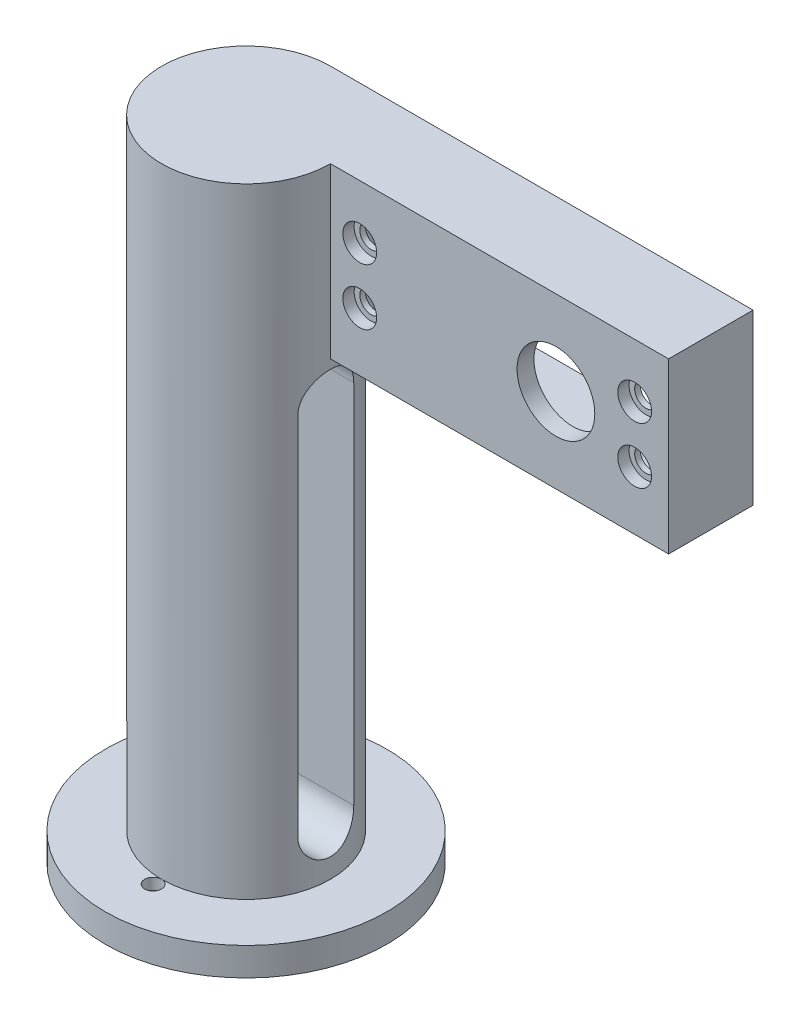
SolidWorks part; units mm, degrees
ref_plane "Front Plane" through (0, 0, 0) normal (0, 0, 1) x (1, 0, 0)
ref_plane "Top Plane" through (0, 0, 0) normal (0, 1, 0) x (1, 0, 0)
ref_plane "Right Plane" through (0, 0, 0) normal (1, 0, 0) x (0, 0, -1)
sketch "Sketch1" plane through (0, 0, 0) normal (0, 1, 0) x (1, 0, 0)
  circle A0 centre (0, 0) radius 25
  dimension "D1" = 50
extrude "Boss-Extrude1" add sketch "Sketch1" along normal blind 5 contours A0
sketch "Sketch2" plane through (0, 5, 0) normal (0, 1, 0) x (1, 0, 0)
  circle A0 centre (0, 0) radius 15
extrude "Boss-Extrude2" add sketch "Sketch2" along normal blind 95 contours A0
sketch "Sketch5" plane through (0, 100, 0) normal (0, 1, 0) x (1, 0, 0)
  line L5 (75, 0) -> (15, 0)
  line L6 (0, 15) -> (75, 15)
  line L9 (75, 15) -> (75, 0)
  arc A4 (0, 15) -> (15, 0) centre (0, 0) ccw
  circle A5 centre (0, 0) radius 15 construction
  circle A6 centre (0, 0) radius 15 construction
  point P2 (0, 0)
  point P20 (0, 0)
extrude "Boss-Extrude4" add sketch "Sketch5" along normal mid plane 30 contours L5 A4 L6 L9
sketch "Sketch10" plane through (0, 0, 0) normal (0, 0, 1) x (1, 0, 0)
  line L0 (15, 100) -> (55, 100) construction
  line L1 (15, 115) -> (15, 85) construction
  line L2 (16.68, 110.4) -> (16.68, 90.4)
  line L3 (16.68, 90.4) -> (72.68, 90.4)
  line L4 (72.68, 90.4) -> (72.68, 110.4)
  line L5 (72.68, 110.4) -> (16.68, 110.4)
  circle A0 centre (55, 100) radius 6.5
  point P5 (0, 100)
  point P6 (68.98, 95.4)
  point P7 (68.98, 105.4)
  point P8 (20.18, 105.4)
  point P9 (20.18, 95.4)
  point P10 (16.68, 90.4)
  point P11 (72.68, 90.4)
  point P12 (72.68, 110.4)
  point P34 (16.68, 110.4)
  dimension "D1" = 40
  dimension "D2" = 15
ref_point "Point1"
sketch "Sketch13" plane through (0, 0, 0) normal (1, 0, 0) x (0, 0, -1)
  line L0 (0, 0) -> (0, 115) construction
  line L1 (0, 78.4433) -> (0, 13.4433) construction
  line L4 (4.9574, 78.4433) -> (4.9574, 13.4433)
  line L5 (-4.9574, 78.4433) -> (-4.9574, 13.4433)
  arc A2 (4.9574, 78.4433) -> (-4.9574, 78.4433) centre (0, 78.4433) ccw
  arc A3 (-4.9574, 13.4433) -> (4.9574, 13.4433) centre (0, 13.4433) ccw
  point P6 (0, 45.9433)
  dimension "D1" = 65
extrude "Cut-Extrude1" cut sketch "Sketch13" against normal mid plane 40
sketch "Sketch15" plane through (0, 0, -15) normal (0, 0, -1) x (-1, 0, 0)
  line L0 (-72.68, 110.9) -> (-16.68, 110.9)
  line L5 (-16.68, 110.9) -> (-16.68, 89.9)
  line L6 (-16.68, 89.9) -> (-72.68, 89.9)
  line L7 (-72.68, 89.9) -> (-72.68, 110.9)
  point P6 (-72.68, 110.9)
  point P8 (-16.68, 89.9)
  point P11 (-16.68, 110.9)
  point P28 (-72.68, 89.9)
extrude "Cut-Extrude3" cut sketch "Sketch15" against normal blind 12
sketch "Sketch17" plane through (0, 0, -3) normal (0, 0, -1) x (-1, 0, 0)
  circle A0 centre (-68.98, 105.4) radius 2
  circle A1 centre (-68.98, 95.4) radius 2
  circle A2 centre (-20.18, 105.4) radius 2
  circle A3 centre (-20.18, 95.4) radius 2
  circle A4 centre (-55, 100) radius 6.9
extrude "Cut-Extrude4" cut sketch "Sketch17" against normal blind 5
sketch "Sketch20" plane through (0, 0, 0) normal (0, 0, 1) x (1, 0, 0)
  circle A0 centre (20.18, 105.4) radius 3
  circle A1 centre (20.18, 95.4) radius 3
  circle A2 centre (68.98, 105.4) radius 3
  circle A3 centre (68.98, 95.4) radius 3
extrude "Cut-Extrude5" cut sketch "Sketch20" against normal blind 2
ref_plane "Plane1" through (0, 100, 0) normal (0, 1, 0) x (1, 0, 0)
sketch "Sketch21" plane through (0, 100, 0) normal (0, 1, 0) x (1, 0, 0)
  point P0 (0, 0)
sketch "Sketch22" plane through (0, 0, 0) normal (0, -1, 0) x (1, 0, 0)
  circle A1 centre (0, 0) radius 3
  circle A2 centre (0, 16.5) radius 1.5
  circle A3 centre (0, -16.5) radius 1.5
  point P3 (0, 16.5)
  point P5 (0, -16.5)
extrude "Cut-Extrude6" cut sketch "Sketch22" against normal blind 10
sketch "Sketch23" plane through (0, 0, 0) normal (0, -1, 0) x (1, 0, 0)
  line L0 (0, 15) -> (0, -15) construction
  line L1 (4.75, 15) -> (4.75, -15)
  line L2 (-4.75, 15) -> (-4.75, -15)
  arc A0 (4.75, 15) -> (-4.75, 15) centre (0, 15) ccw
  arc A1 (-4.75, -15) -> (4.75, -15) centre (0, -15) ccw
  point P2 (0, 0)
  point P10 (0, 16.5)
  dimension "D1" = 16.5
extrude "Cut-Extrude7" cut sketch "Sketch23" against normal blind 3
sketch "Sketch24" plane through (0, 3, 0) normal (0, -1, 0) x (1, 0, 0)
  circle A0 centre (0, 0) radius 6.5
extrude "Cut-Extrude8" cut sketch "Sketch24" along normal blind 3
